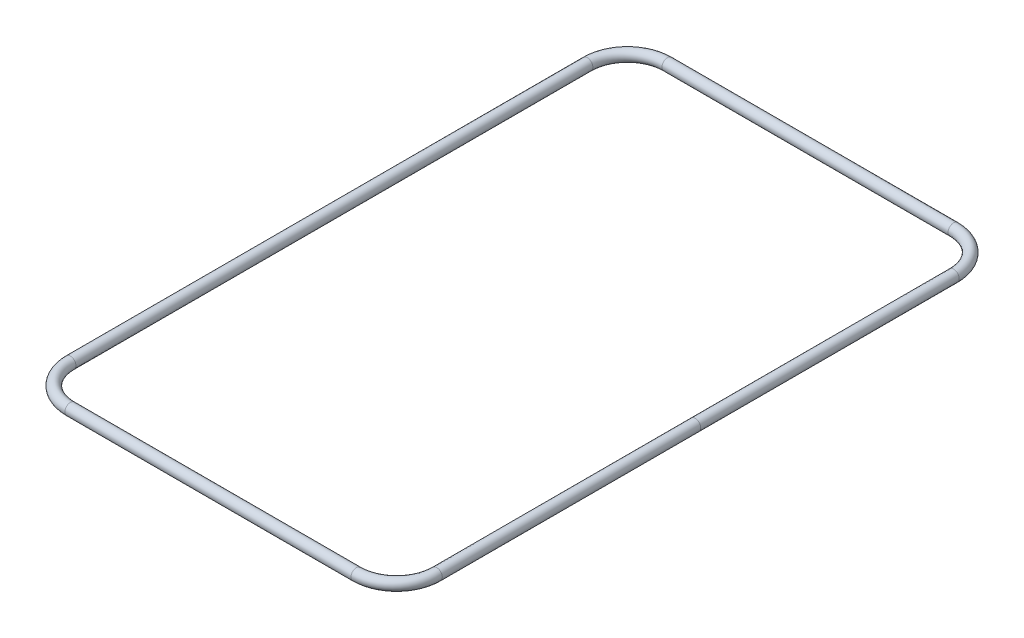
SolidWorks part; units mm, degrees
ref_plane "Front Plane" through (0, 0, 0) normal (0, 0, 1) x (1, 0, 0)
ref_plane "Top Plane" through (0, 0, 0) normal (0, 1, 0) x (1, 0, 0)
ref_plane "Right Plane" through (0, 0, 0) normal (1, 0, 0) x (0, 0, -1)
sketch "BaseDimensions" plane through (0, 0, 0) normal (0, 1, 0) x (1, 0, 0)
  line L0 (0, -101.6) -> (0, 101.6) construction
  line L1 (63.5, 0) -> (-63.5, 0) construction
  point P5 (0, 0)
  point P6 (0, 0)
  dimension "D1" = 203.2
  dimension "D2" = 127
sketch "O-RingPath" plane through (0, 0, 0) normal (0, 1, 0) x (1, 0, 0)
  line L0 (45.2965, -94.5388) -> (-45.2965, -94.5388)
  line L1 (57.9965, -81.8388) -> (57.9965, 81.8388)
  line L2 (0, 0) -> (0, -94.5388) construction
  line L3 (57.9965, 0) -> (0, 0) construction
  line L4 (-57.9965, -81.8388) -> (-57.9965, 81.8388)
  line L5 (45.2965, 94.5388) -> (-45.2965, 94.5388)
  arc A0 (45.2965, -94.5388) -> (57.9965, -81.8388) centre (45.2965, -81.8388) ccw
  arc A1 (-45.2965, -94.5388) -> (-57.9965, -81.8388) centre (-45.2965, -81.8388) cw
  arc A2 (-45.2965, 94.5388) -> (-57.9965, 81.8388) centre (-45.2965, 81.8388) ccw
  arc A3 (45.2965, 94.5388) -> (57.9965, 81.8388) centre (45.2965, 81.8388) cw
  point P17 (-57.9965, 0)
  dimension "D2" = 12.7
  dimension "D3" = 7.0612
sketch "O-RingProfile" plane through (0, 0, 0) normal (0, 0, 1) x (1, 0, 0)
  circle A0 centre (57.9965, 0) radius 1.7653
  dimension "D1" = 3.5306
sweep "Sweep2" add profiles "O-RingProfile" path "O-RingPath"
ref_plane "TopOfRing" through (0, 1.7653, 0) normal (0, 1, 0) x (1, 0, 0)
ref_plane "BottomOfRing" through (0, -1.7653, 0) normal (0, -1, 0) x (-1, 0, 0)
equation "\"D1@O-RingProfile\" = \"O-Ring_CS@BladderAssembly.SLDASM\""
equation "\"D1@BaseDimensions\" = \"BaseLength@BladderAssembly.SLDASM\""
equation "\"D2@BaseDimensions\"=\"BaseWidth@BladderAssembly.SLDASM\""
equation "\"D3@O-RingPath\"=2* \"O-Ring_CS@BladderAssembly.SLDASM\" "
